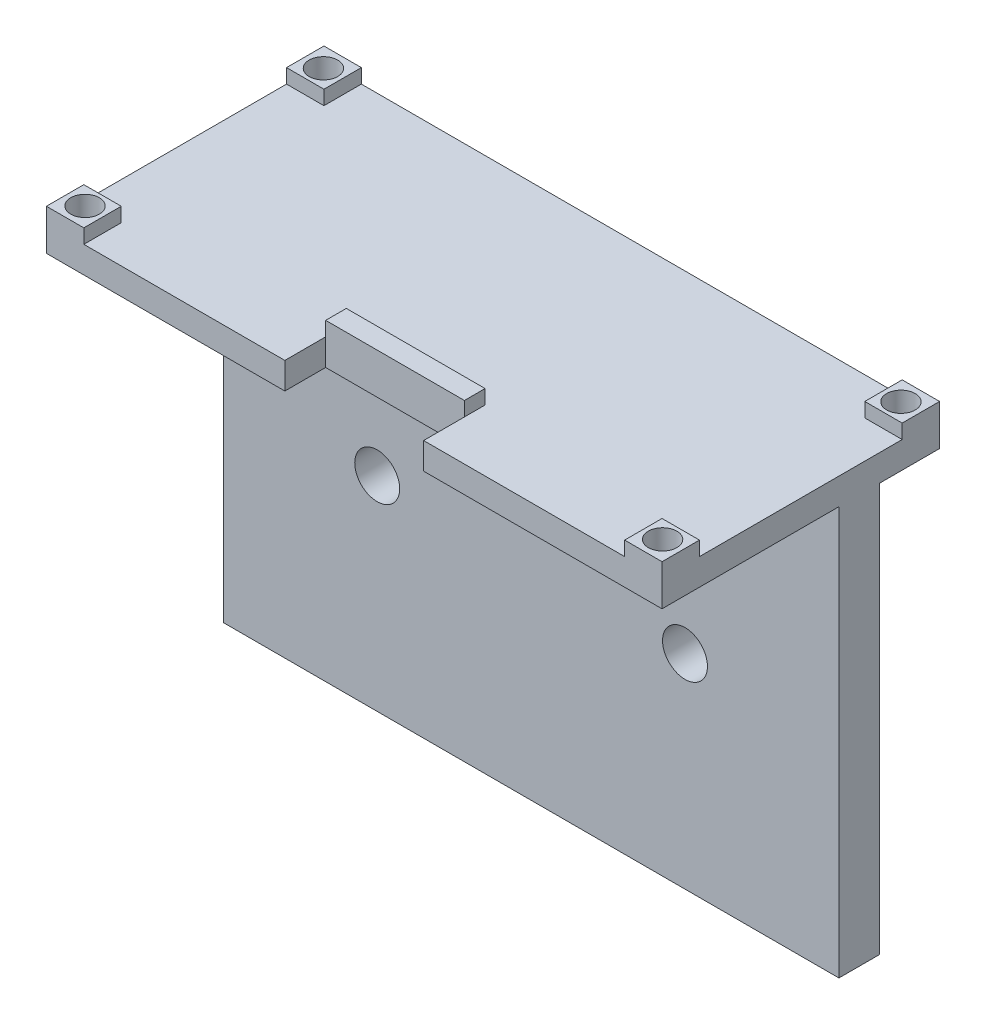
SolidWorks part; units mm, degrees
ref_plane "Alzado" through (0, 0, 0) normal (0, 0, 1) x (1, 0, 0)
ref_plane "Planta" through (0, 0, 0) normal (0, 1, 0) x (1, 0, 0)
ref_plane "Vista lateral" through (0, 0, 0) normal (1, 0, 0) x (0, 0, -1)
sketch "Croquis1" plane through (0, 0, 0) normal (0, 1, 0) x (1, 0, 0)
  line L1 (0, 0) -> (45.25, 0)
  line L2 (0, 0) -> (0, 20.4)
  line L3 (0, 20.4) -> (45.25, 20.4)
  line L4 (45.25, 0) -> (45.25, 20.4)
  dimension "D1" = 20.4
  dimension "D2" = 45.25
extrude "Saliente-Extruir1" add sketch "Croquis1" along normal blind 3
sketch "Croquis2" plane through (0, 3, 0) normal (0, 1, 0) x (1, 0, 0)
  line L0 (0, 0) -> (45.25, 0) construction
  line L1 (17.525, 3) -> (27.725, 3)
  line L2 (17.525, 3) -> (17.525, 0)
  line L3 (17.525, 0) -> (27.725, 0)
  line L4 (27.725, 3) -> (27.725, 0)
  point P6 (22.625, 0)
  point P7 (22.625, 0)
  dimension "D1" = 10.2
  dimension "D2" = 3
extrude "Cortar-Extruir1" cut sketch "Croquis2" against normal through all
sketch "Croquis3" plane through (0, 3, 0) normal (0, 1, 0) x (1, 0, 0)
  line L0 (45.25, 20.4) -> (0, 20.4) construction
  line L5 (42.5, 0) -> (27.725, 0)
  line L6 (27.725, 0) -> (27.725, 4.5185)
  line L7 (2.75, 20.4) -> (2.75, 17.65)
  line L8 (2.75, 17.65) -> (0, 17.65)
  line L9 (0, 20.4) -> (0, 0) construction
  line L10 (0, 2.75) -> (2.75, 2.75)
  line L11 (2.75, 2.75) -> (2.75, 0)
  line L12 (0, 0) -> (17.525, 0) construction
  line L13 (22.625, 20.4) -> (22.625, 3) construction
  line L14 (27.725, 3) -> (17.525, 3) construction
  line L15 (42.5, 2.75) -> (42.5, 0)
  line L16 (45.25, 2.75) -> (42.5, 2.75)
  line L17 (42.5, 17.65) -> (45.25, 17.65)
  line L18 (42.5, 20.4) -> (42.5, 17.65)
  line L19 (0, 17.65) -> (0, 2.75)
  line L20 (2.75, 20.4) -> (42.5, 20.4)
  line L21 (2.75, 0) -> (17.525, 0)
  line L22 (17.525, 0) -> (17.525, 4.5185)
  line L23 (27.725, 4.5185) -> (17.525, 4.5185)
  line L24 (45.25, 2.75) -> (45.25, 17.65)
  dimension "D1" = 2.75
  dimension "D2" = 2.75
  dimension "D3" = 2.75
  dimension "D4" = 2.75
  dimension "D5" = 1.5185
extrude "Cortar-Extruir2" cut sketch "Croquis3" against normal blind 1.05
sketch "Croquis5" plane through (0, 3, 0) normal (0, 1, 0) x (1, 0, 0)
  line L0 (0, 10.2) -> (45.25, 10.2) construction
  line L1 (45.25, 20.4) -> (42.5, 20.4) construction
  line L2 (45.25, 0) -> (45.25, 2.75) construction
  line L3 (22.625, 20.4) -> (22.625, 0) construction
  line L4 (45.25, 0) -> (0, 0) construction
  line L5 (0, 17.65) -> (0, 2.75) construction
  line L7 (45.25, 2.75) -> (45.25, 17.65) construction
  circle A0 centre (43.85, 18.96) radius 1.05
  circle A3 centre (1.4, 18.96) radius 1.05
  circle A4 centre (43.85, 1.44) radius 1.05
  circle A5 centre (1.4, 1.44) radius 1.05
  dimension "D3" = 2.1
  dimension "D1" = 1.44
  dimension "D2" = 1.4
extrude "Cortar-Extruir4" cut sketch "Croquis5" against normal through all
sketch "Croquis6" plane through (0, 0, 0) normal (0, -1, 0) x (1, 0, 0)
  line L0 (17.525, -3) -> (0, -3)
  line L1 (0, -20.4) -> (0, 0) construction
  line L2 (0, -3) -> (0, -18)
  line L3 (0, -18) -> (45.25, -18)
  line L4 (45.25, 0) -> (45.25, -20.4) construction
  line L5 (45.25, -18) -> (45.25, -3)
  line L6 (45.25, -3) -> (17.525, -3)
  dimension "D1" = 15
extrude "Saliente-Extruir2" add sketch "Croquis6" along normal blind 30
sketch "Croquis8" plane through (0, 0, -3) normal (0, 0, 1) x (1, 0, 0)
  line L1 (0, -30) -> (45.25, -30)
  line L2 (0, -30) -> (0, 0)
  line L3 (0, 0) -> (45.25, 0)
  line L4 (45.25, -30) -> (45.25, 0)
extrude "Cortar-Extruir5" cut sketch "Croquis8" against normal blind 10
sketch "Croquis10" plane through (0, 0, -18) normal (0, 0, -1) x (-1, 0, 0)
  line L0 (-22.625, 0) -> (-22.625, -30) construction
  line L1 (-45.25, 0) -> (0, 0) construction
  line L2 (0, -30) -> (-45.25, -30) construction
  line L3 (0, -15) -> (-45.25, -15) construction
  line L4 (0, -30) -> (0, 0) construction
  line L5 (-45.25, -30) -> (-45.25, 0) construction
  line L6 (0, -30) -> (-22.625, -30) construction
  line L7 (-11.3125, -30) -> (-11.3125, 0) construction
  line L8 (0, 0) -> (-0.9747, 0) construction
  line L9 (-33.9375, -30) -> (-33.9375, 0) construction
  circle A0 centre (-11.3125, -15) radius 1.65
  circle A1 centre (-33.9375, -15) radius 1.65
  dimension "D1" = 3.3
  dimension "D2" = 3.3
  dimension "D3" = 11.3125
  dimension "D4" = 15
extrude "Cortar-Extruir6" cut sketch "Croquis10" against normal through all
sketch "Croquis11" plane through (0, 0, -18) normal (0, 0, -1) x (-1, 0, 0)
  line L1 (0, -30) -> (-45.25, -30)
  line L2 (0, -30) -> (0, 0)
  line L3 (0, 0) -> (-45.25, 0)
  line L4 (-45.25, -30) -> (-45.25, 0)
extrude "Cortar-Extruir7" cut sketch "Croquis11" against normal blind 2
